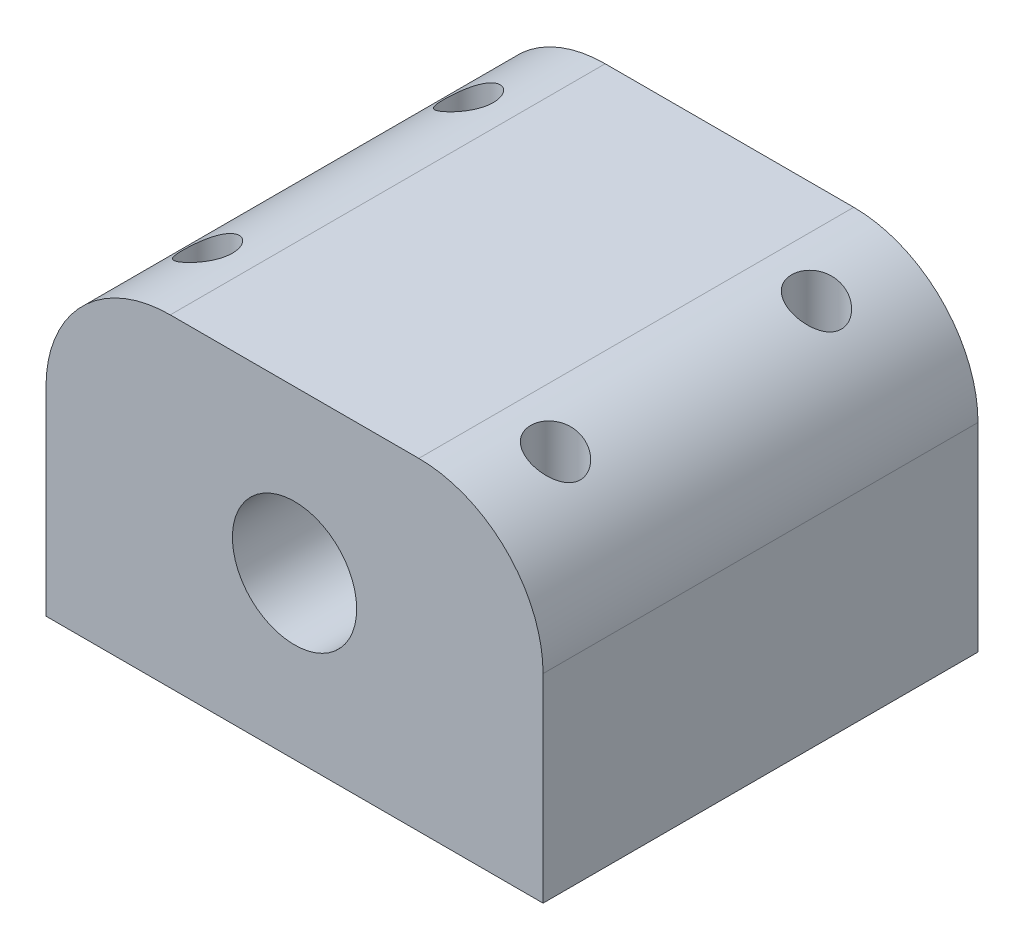
SolidWorks part; units mm, degrees
material "1060 Alloy"
ref_plane "Front Plane" through (0, 0, 0) normal (0, 0, 1) x (1, 0, 0)
ref_plane "Top Plane" through (0, 0, 0) normal (0, 1, 0) x (1, 0, 0)
ref_plane "Right Plane" through (0, 0, 0) normal (1, 0, 0) x (0, 0, -1)
sketch "Sketch1" plane through (0, 0, 0) normal (0, 0, 1) x (1, 0, 0)
  line L1 (30.325, 21.8) -> (-9.675, 21.8)
  line L2 (30.325, 21.8) -> (30.325, -4.2)
  line L3 (30.325, -4.2) -> (-9.675, -4.2)
  line L4 (-9.675, 21.8) -> (-9.675, -4.2)
  line L5 (30.325, 21.8) -> (-9.675, -4.2) construction
  line L6 (30.325, -4.2) -> (-9.675, 21.8) construction
  point P0 (10.325, 8.8)
  dimension "D1" = 40
  dimension "D2" = 26
extrude "Boss-Extrude1" add sketch "Sketch1" along normal blind 35 contours L1 L4 L3 L2
sketch "Sketch2" plane through (0, 0, 35) normal (0, 0, 1) x (1, 0, 0)
  line L0 (-9.675, 21.8) -> (-9.675, -4.2) construction
  line L1 (30.325, -4.2) -> (-9.675, -4.2) construction
  circle A0 centre (10.325, 8.8) radius 5
  dimension "D1" = 10
  dimension "D2" = 20
  dimension "D3" = 13
extrude "Cut-Extrude1" cut sketch "Sketch2" against normal blind 45
fillet "Fillet1" radius 10 2 edges at (-9.675, 21.8, 17.5) (30.325, 21.8, 17.5)
sketch "Sketch3" plane through (0, 21.8, 0) normal (0, 1, 0) x (1, 0, 0)
  line L0 (0.325, 0) -> (-9.675, 0) construction
  line L1 (-9.675, -35) -> (-9.675, 0) construction
  line L2 (-9.675, -35) -> (0.325, -35) construction
  line L3 (30.325, 0) -> (30.325, -35) construction
  line L4 (30.325, 0) -> (20.325, 0) construction
  line L5 (20.325, -35) -> (30.325, -35) construction
  circle A0 centre (-3.675, -7) radius 2
  circle A1 centre (24.325, -7) radius 2
  circle A2 centre (-3.675, -28) radius 2
  circle A3 centre (24.325, -28) radius 2
  dimension "D5" = 4
  dimension "D6" = 4
  dimension "D7" = 4
  dimension "D8" = 4
  dimension "D1" = 7
  dimension "D2" = 6
  dimension "D3" = 6
  dimension "D4" = 7
  dimension "D9" = 6
  dimension "D10" = 7
  dimension "D11" = 6
  dimension "D12" = 7
extrude "Cut-Extrude2" cut sketch "Sketch3" against normal blind 26
